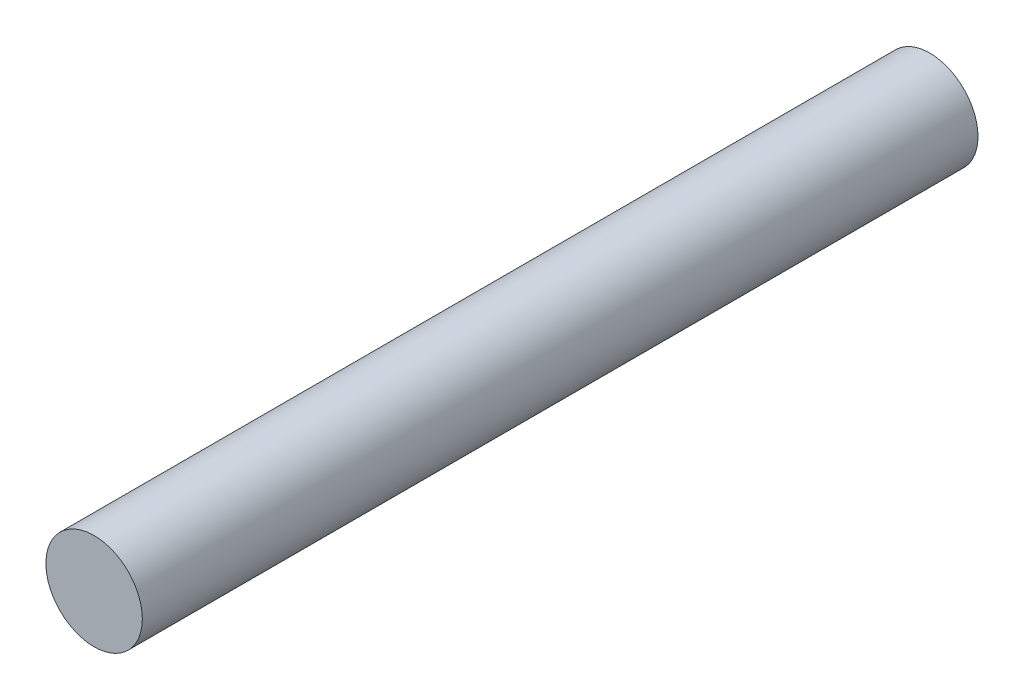
SolidWorks part; units mm, degrees
ref_plane "前视基准面" through (0, 0, 0) normal (0, 0, 1) x (1, 0, 0)
ref_plane "上视基准面" through (0, 0, 0) normal (0, 1, 0) x (1, 0, 0)
ref_plane "右视基准面" through (0, 0, 0) normal (1, 0, 0) x (0, 0, -1)
other "Configuration Table"
sketch "草图1" plane through (0, 0, 0) normal (0, 0, 1) x (1, 0, 0)
  circle A0 centre (0, 0) radius 7.5
  dimension "D1" = 15
extrude "凸台-拉伸1" add sketch "草图1" along normal blind 130
